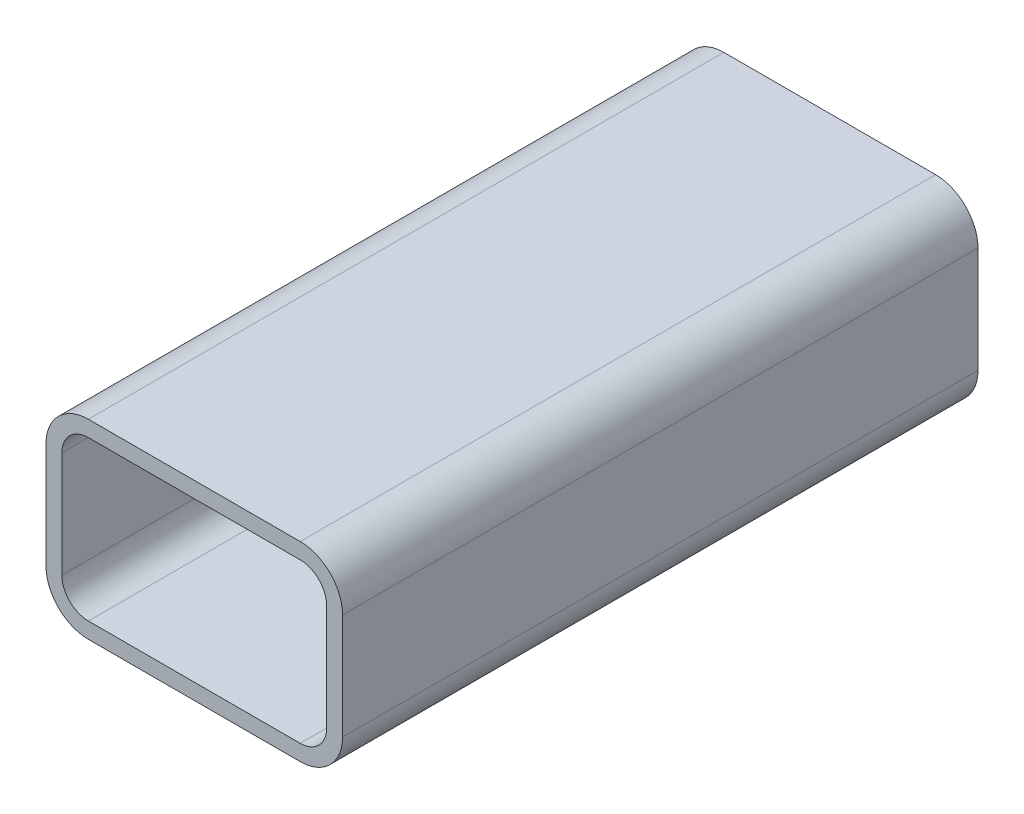
SolidWorks part; units mm, degrees
ref_plane "Front Plane" through (0, 0, 0) normal (0, 0, 1) x (1, 0, 0)
ref_plane "Top Plane" through (0, 0, 0) normal (0, 1, 0) x (1, 0, 0)
ref_plane "Right Plane" through (0, 0, 0) normal (1, 0, 0) x (0, 0, -1)
sketch "Sketch1" plane through (0, 0, 0) normal (0, 0, 1) x (1, 0, 0)
  line L1 (-20, 15) -> (20, 15)
  line L2 (-25, 10) -> (-25, -10)
  line L3 (-20, -15) -> (20, -15)
  line L4 (25, 10) -> (25, -10)
  line L5 (-25, 15) -> (25, -15) construction
  line L6 (-25, -15) -> (25, 15) construction
  arc A0 (-25, -10) -> (-20, -15) centre (-20, -10) ccw
  arc A1 (20, -15) -> (25, -10) centre (20, -10) ccw
  arc A2 (20, 15) -> (25, 10) centre (20, 10) cw
  arc A3 (-20, 15) -> (-25, 10) centre (-20, 10) ccw
  point P0 (0, 0)
  dimension "D3" = 5
  dimension "D1" = 50
  dimension "D2" = 30
extrude "Extrude-Thin1" add sketch "Sketch1" along normal mid plane 120 thin contours L1 A2 L4 A1 L3 A0 L2 A3 thin type one direction wall 3
